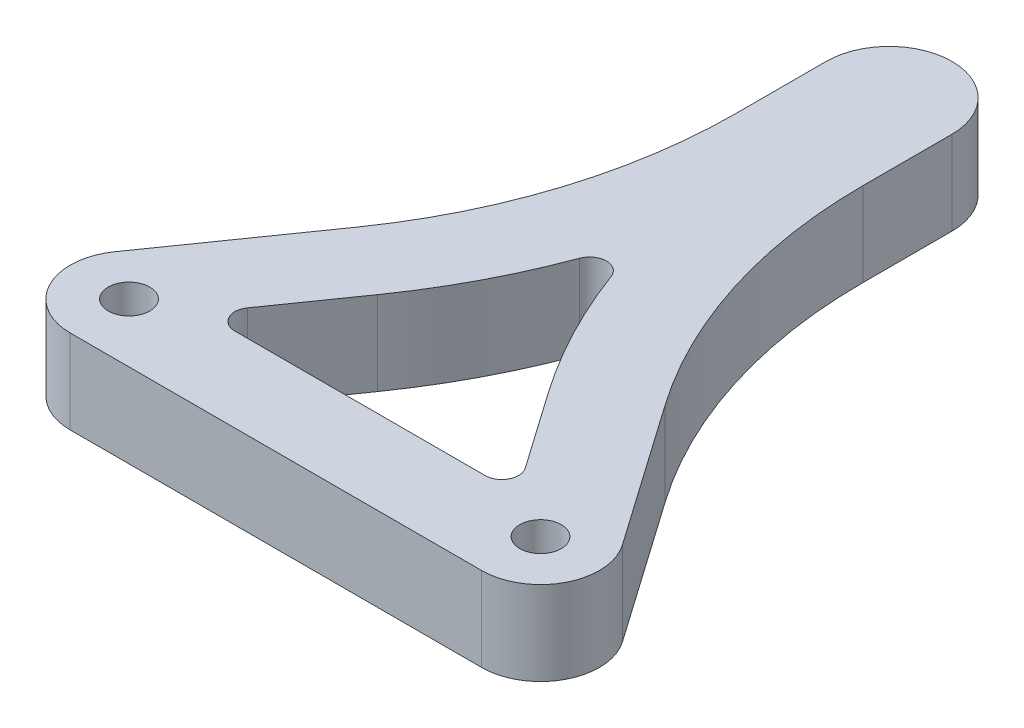
SolidWorks part; units mm, degrees
ref_plane "Спереди" through (0, 0, 0) normal (0, 0, 1) x (1, 0, 0)
ref_plane "Сверху" through (0, 0, 0) normal (0, 1, 0) x (1, 0, 0)
ref_plane "Справа" through (0, 0, 0) normal (1, 0, 0) x (0, 0, -1)
sketch "Эскиз1" plane through (0, 0, 0) normal (0, 1, 0) x (1, 0, 0)
  line L0 (-24.5, 0) -> (24.5, 0) construction
  line L1 (-7.5, 66) -> (-7.5, 55.4006)
  line L2 (-18.3509, 20.986) -> (-30.2341, 4.015)
  line L3 (0, 66) -> (0, 0) construction
  line L4 (18.3509, 20.986) -> (30.2341, 4.015)
  line L5 (7.5, 66) -> (7.5, 55.4006)
  line L6 (-24.5, -7) -> (24.5, -7)
  line L7 (0, 36.8601) -> (0, 36.8601)
  line L8 (0, 36.8601) -> (0, 36.8601)
  line L9 (10.1594, 15.2502) -> (18.7371, 3)
  line L10 (-18.7371, 3) -> (18.7371, 3)
  line L11 (-10.1594, 15.2502) -> (-18.7371, 3)
  circle A0 centre (-24.5, 0) radius 2.475
  circle A1 centre (24.5, 0) radius 2.475
  arc A2 (7.5, 66) -> (-7.5, 66) centre (0, 66) ccw
  arc A3 (-30.2341, 4.015) -> (-24.5, -7) centre (-24.5, 0) ccw
  arc A4 (24.5, -7) -> (30.2341, 4.015) centre (24.5, 0) ccw
  arc A5 (-18.3509, 20.986) -> (-7.5, 55.4006) centre (-67.5, 55.4006) ccw
  arc A6 (18.3509, 20.986) -> (7.5, 55.4006) centre (67.5, 55.4006) cw
  arc A7 (-10.1594, 15.2502) -> (0, 36.8601) centre (-67.5, 55.4006) ccw
  arc A8 (0, 36.8601) -> (0, 36.8601) centre (0, 36.8601) cw
  arc A9 (10.1594, 15.2502) -> (0, 36.8601) centre (67.5, 55.4006) cw
  arc A10 (18.7371, 3) -> (18.7371, 3) centre (18.7371, 3) ccw
  arc A11 (-18.7371, 3) -> (-18.7371, 3) centre (-18.7371, 3) ccw
  dimension "D1" = 4.95
  dimension "D3" = 15
  dimension "D5" = 14
  dimension "D6" = 60
  dimension "D2" = 49
  dimension "D4" = 66
  dimension "D7" = 145
  dimension "D8" = 10
extrude "Бобышка-Вытянуть1" add sketch "Эскиз1" along normal blind 10
fillet "Скругление1" radius 2 3 edges at (0, 5, -36.8601) (18.7371, 5, -3) (-18.7371, 5, -3)
